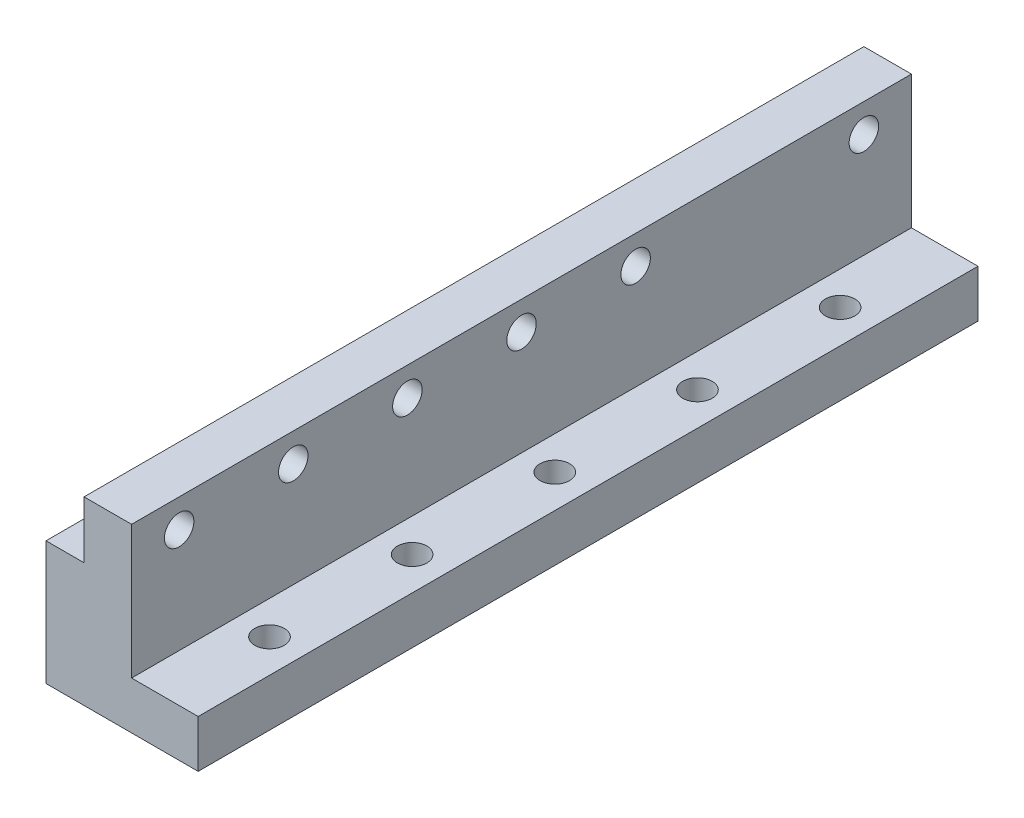
SolidWorks part; units mm, degrees
ref_plane "前基準面" through (0, 0, 0) normal (0, 0, 1) x (1, 0, 0)
ref_plane "上基準面" through (0, 0, 0) normal (0, 1, 0) x (1, 0, 0)
ref_plane "右基準面" through (0, 0, 0) normal (1, 0, 0) x (0, 0, -1)
sketch "草圖1" plane through (0, 0, 0) normal (0, 0, 1) x (1, 0, 0)
  line L0 (4, 6) -> (4, 0)
  line L1 (4, 0) -> (0, 0)
  line L2 (0, 0) -> (0, -13)
  line L3 (0, -13) -> (16, -13)
  line L4 (16, -13) -> (16, -8)
  line L5 (16, -8) -> (9, -8)
  line L6 (9, -8) -> (9, 6)
  line L7 (9, 6) -> (4, 6)
  dimension "D1" = 5
  dimension "D2" = 4
  dimension "D3" = 6
  dimension "D4" = 14
  dimension "D5" = 7
  dimension "D6" = 5
extrude "填料-伸長1" add sketch "草圖1" along normal blind 82
sketch "草圖2" plane through (0, -8, 0) normal (0, 1, 0) x (1, 0, 0)
  line L2 (16, -82) -> (9, -82) construction
  circle A3 centre (12.5, -71) radius 1.55
  point P0 (12.5, -82)
  dimension "D12" = 3.1
  dimension "D13" = 11
extrude "除料-伸長1" cut sketch "草圖2" against normal through all
sketch "草圖3" plane through (4, 0, 0) normal (-1, 0, 0) x (0, 0, 1)
  line L0 (0, 3) -> (82, 3) construction
  line L2 (0, 6) -> (0, 0) construction
  line L3 (82, 6) -> (82, 0) construction
  circle A0 centre (5, 3) radius 1.55
  circle A1 centre (29, 3) radius 1.55
  circle A2 centre (41, 3) radius 1.55
  circle A3 centre (53, 3) radius 1.55
  circle A4 centre (65, 3) radius 1.55
  circle A5 centre (77, 3) radius 1.55
  dimension "D2" = 3.1
  dimension "D3" = 3.1
  dimension "D4" = 3.1
  dimension "D5" = 3.1
  dimension "D6" = 3.1
  dimension "D7" = 3.1
  dimension "D8" = 5
  dimension "D9" = 5
  dimension "D10" = 12
  dimension "D11" = 12
  dimension "D12" = 12
  dimension "D13" = 12
extrude "除料-伸長2" cut sketch "草圖3" against normal through all
pattern_linear "直線複製排列1" count 5 spacing 15 along (0, 0, -1) of "除料-伸長1"
